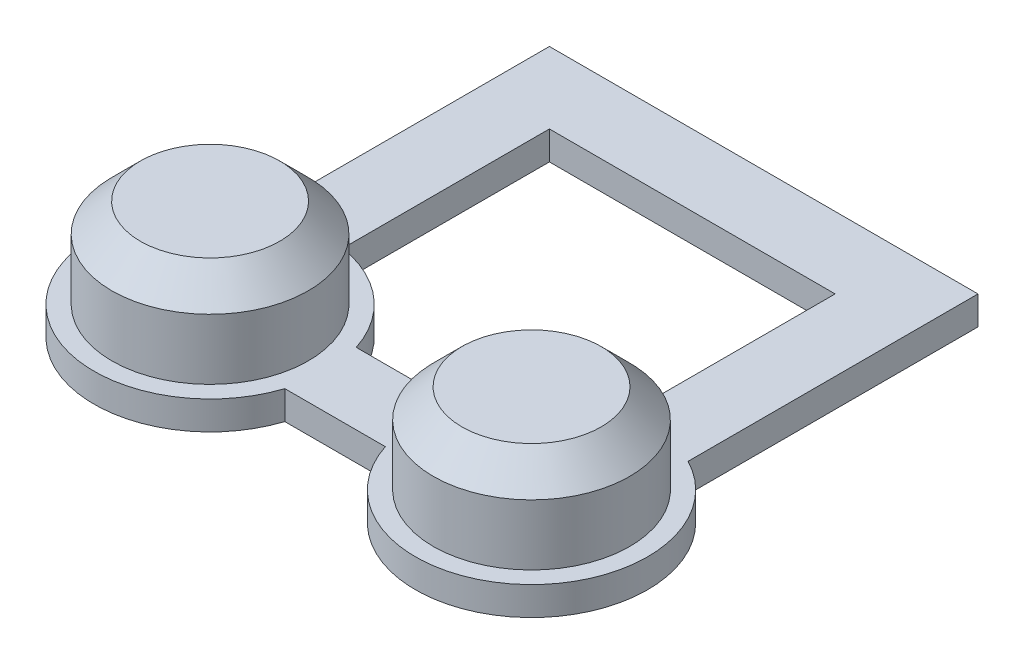
SolidWorks part; units mm, degrees
ref_plane "前视基准面" through (0, 0, 0) normal (0, 0, 1) x (1, 0, 0)
ref_plane "上视基准面" through (0, 0, 0) normal (0, 1, 0) x (1, 0, 0)
ref_plane "右视基准面" through (0, 0, 0) normal (1, 0, 0) x (0, 0, -1)
other "Configuration Table"
sketch "草图1" plane through (0, 0, 0) normal (0, 1, 0) x (1, 0, 0)
  line L0 (-4.8357, 0) -> (3.8453, 0) construction
  line L1 (0, 9.3886) -> (0, -8.4222) construction
  line L2 (-1.3377, 0.75) -> (1.3377, 0.75)
  line L3 (-1.3377, -0.75) -> (1.3377, -0.75)
  circle A0 centre (-4.5, 0) radius 3.25
  circle A1 centre (4.5, 0) radius 3.25
  dimension "D1" = 6.5
  dimension "D2" = 9
  dimension "D3" = 1.5
extrude "凸台-拉伸1" add sketch "草图1" along normal blind 0.8 contours A0 | A1 L2 A0 L3 | A1
sketch "草图2" plane through (0, 0.8, 0) normal (0, 1, 0) x (1, 0, 0)
  circle A0 centre (-4.5, 0) radius 2.75
  circle A1 centre (4.5, 0) radius 2.75
  dimension "D1" = 5.5
extrude "凸台-拉伸2" add sketch "草图2" along normal blind 2.5
chamfer "倒角1" distance 0.8 angle 45 2 edges at (4.5, 3.3, 2.75) (-4.5, 3.3, 2.75)
sketch "草图3" plane through (0, 0, 0) normal (0, -1, 0) x (1, 0, 0)
  circle A0 centre (-4.5, 0) radius 1
  circle A1 centre (4.5, 0) radius 1
  dimension "D1" = 2
extrude "凸台-拉伸3" add sketch "草图3" along normal blind 0.45
sketch "草图4" plane through (0, 0, 0) normal (0, -1, 0) x (1, 0, 0)
  line L1 (-6, 1) -> (6, 1)
  line L2 (-6, 1) -> (-6, -11)
  line L3 (-6, -11) -> (6, -11)
  line L4 (6, 1) -> (6, -11)
  line L5 (-4, -1) -> (4, -1)
  line L6 (-4, -1) -> (-4, -9)
  line L7 (-4, -9) -> (4, -9)
  line L8 (4, -1) -> (4, -9)
  dimension "D1" = 12
  dimension "D2" = 8
  dimension "D3" = 8
  dimension "D4" = 12
  dimension "D5" = 6
  dimension "D6" = 1
  dimension "D7" = 2
  dimension "D8" = 2
extrude "凸台-拉伸4" add sketch "草图4" against normal blind 0.8
